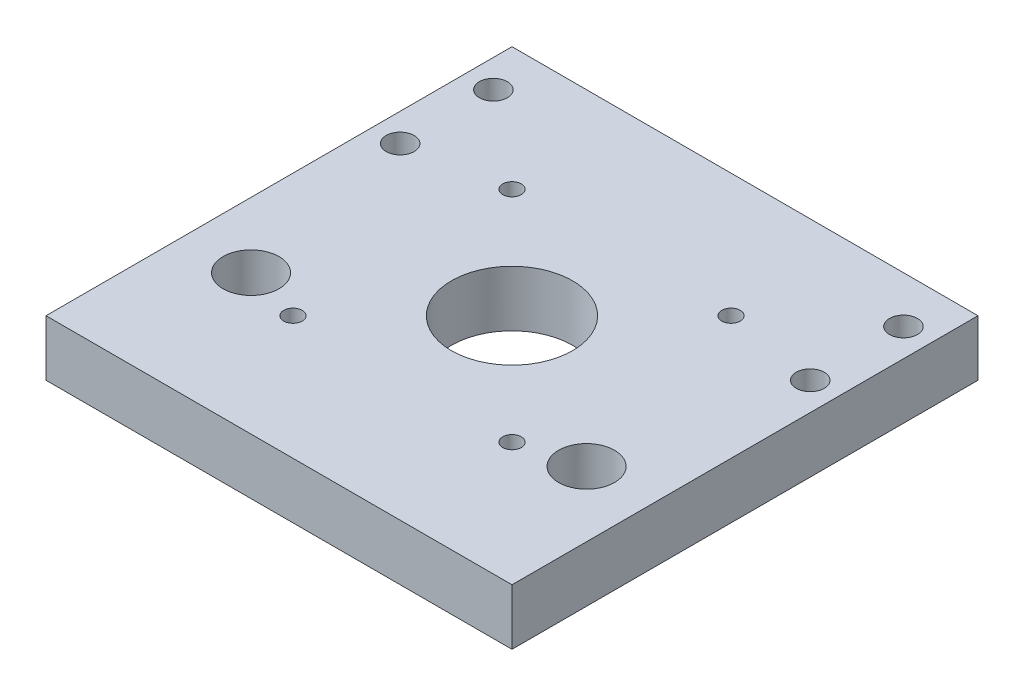
SolidWorks part; units mm, degrees
material "Beech"
ref_plane "Front Plane" through (0, 0, 0) normal (0, 0, 1) x (1, 0, 0)
ref_plane "Top Plane" through (0, 0, 0) normal (0, 1, 0) x (1, 0, 0)
ref_plane "Right Plane" through (0, 0, 0) normal (1, 0, 0) x (0, 0, -1)
sketch "Sketch1" plane through (0, 0, 0) normal (0, 1, 0) x (1, 0, 0)
  line L0 (0, -6.8113) -> (0, 29.9116) construction
  line L1 (-50, 30) -> (50, 30)
  line L2 (-54.3903, 0) -> (55.5839, 0) construction
  line L7 (-50, 30) -> (-50, -70)
  line L8 (-50, -70) -> (50, -70)
  line L9 (50, -70) -> (50, 30)
  point P0 (0, 0)
  dimension "D1" = 30
  dimension "D2" = 50
  dimension "D3" = 100
  dimension "D4" = 100
extrude "Boss-Extrude1" add sketch "Sketch1" along normal blind 12
sketch "Sketch2" plane through (0, 12, 0) normal (0, 1, 0) x (1, 0, 0)
  line L0 (-44, 36.933) -> (-44, -38.3163) construction
  line L1 (44, 34.8909) -> (44, -38.3163) construction
  line L4 (50, 30) -> (-50, 30) construction
  line L5 (-50, 30) -> (-50, -70) construction
  line L6 (50, -70) -> (50, 30) construction
  circle A0 centre (-44, 20) radius 3
  circle A1 centre (-44, 0) radius 3
  circle A2 centre (44, 20) radius 3
  circle A3 centre (44, 0) radius 3
  dimension "D3" = 6
  dimension "D4" = 6
  dimension "D5" = 6
  dimension "D6" = 6
  dimension "D7" = 10
  dimension "D8" = 10
  dimension "D9" = 20
  dimension "D10" = 20
  dimension "D2" = 6
  dimension "D11" = 6
extrude "Cut-Extrude1" cut sketch "Sketch2" against normal up to next
sketch "Sketch3" plane through (0, 12, 0) normal (0, 1, 0) x (1, 0, 0)
  line L0 (0, 33.2699) -> (0, -87.3901) construction
  line L1 (-27.4907, -20) -> (29.5668, -20) construction
  line L2 (-23.5, 3.5) -> (-23.5, -43.5) construction
  line L3 (-23.5, -43.5) -> (23.5, -43.5) construction
  line L4 (23.5, -43.5) -> (23.5, 3.5) construction
  line L5 (23.5, 3.5) -> (-23.5, 3.5) construction
  line L6 (-50, -70) -> (50, -70) construction
  circle A0 centre (-23.5, -43.5) radius 2
  circle A1 centre (23.5, -43.5) radius 2
  circle A2 centre (23.5, 3.5) radius 2
  circle A3 centre (-23.5, 3.5) radius 2
  circle A4 centre (0, -20) radius 13
  dimension "D1" = 23.5
  dimension "D5" = 4
  dimension "D6" = 4
  dimension "D7" = 4
  dimension "D8" = 4
  dimension "D9" = 26
  dimension "D2" = 23.5
  dimension "D3" = 23.5
  dimension "D4" = 23.5
  dimension "D10" = 50
extrude "Cut-Extrude2" cut sketch "Sketch3" against normal up to next
sketch "Sketch4" plane through (0, 12, 0) normal (0, 1, 0) x (1, 0, 0)
  line L0 (-50, -70) -> (50, -70) construction
  line L1 (0, -42.4453) -> (0, -79.4161) construction
  circle A0 centre (-36, -40) radius 6
  circle A1 centre (36, -40) radius 6
  dimension "D1" = 12
  dimension "D2" = 12
  dimension "D3" = 36
  dimension "D4" = 36
  dimension "D5" = 30
  dimension "D6" = 30
extrude "Cut-Extrude3" cut sketch "Sketch4" against normal up to next
